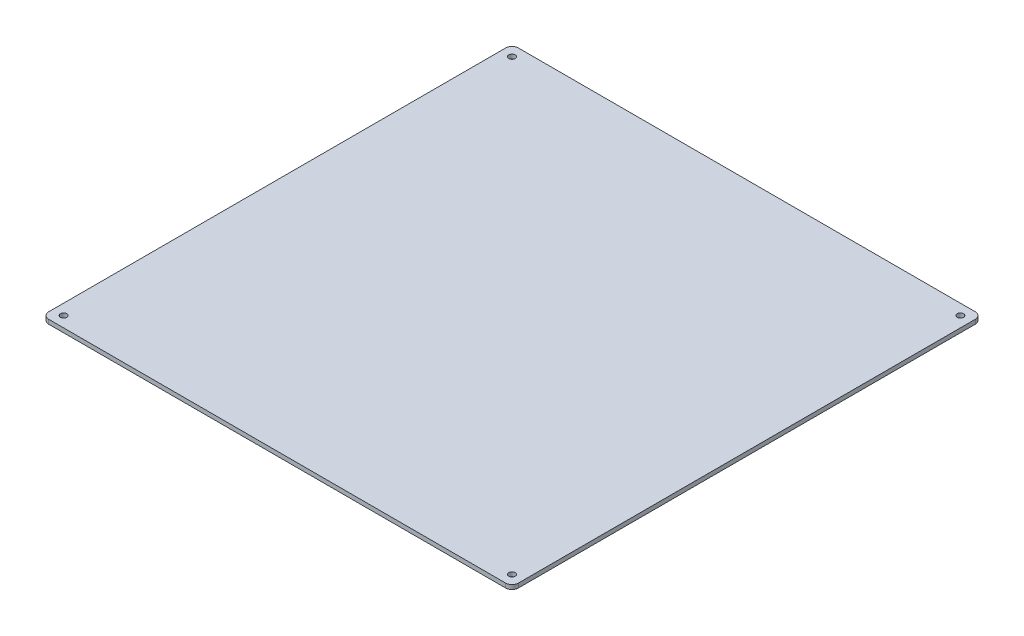
SolidWorks part; units mm, degrees
ref_plane "정면" through (0, 0, 0) normal (0, 0, 1) x (1, 0, 0)
ref_plane "윗면" through (0, 0, 0) normal (0, 1, 0) x (1, 0, 0)
ref_plane "우측면" through (0, 0, 0) normal (1, 0, 0) x (0, 0, -1)
sketch "스케치1" plane through (0, 0, 0) normal (0, 1, 0) x (1, 0, 0)
  line L0 (-109.5, 0) -> (109.5, 0) construction
  line L1 (-109.5, -109.5) -> (109.5, -109.5)
  line L2 (-109.5, -109.5) -> (-109.5, 109.5)
  line L3 (-109.5, 109.5) -> (109.5, 109.5)
  line L4 (109.5, -109.5) -> (109.5, 109.5)
  line L5 (-109.5, -109.5) -> (109.5, 109.5) construction
  line L6 (-109.5, 109.5) -> (109.5, -109.5) construction
  line L7 (-104.5, -104.5) -> (104.5, -104.5) construction
  line L8 (-104.5, -104.5) -> (-104.5, 104.5) construction
  line L9 (-104.5, 104.5) -> (104.5, 104.5) construction
  line L10 (104.5, -104.5) -> (104.5, 104.5) construction
  line L11 (-104.5, -104.5) -> (104.5, 104.5) construction
  line L12 (-104.5, 104.5) -> (104.5, -104.5) construction
  line L13 (0, 109.5) -> (0, -109.5) construction
  circle A0 centre (-104.5, 104.5) radius 1.5
  circle A1 centre (-104.5, -104.5) radius 1.5
  circle A2 centre (104.5, -104.5) radius 1.5
  circle A3 centre (104.5, 104.5) radius 1.5
  point P0 (0, 0)
  point P6 (0, 0)
  dimension "D3" = 3
  dimension "D1" = 219
  dimension "D2" = 209
extrude "보스-돌출1" add sketch "스케치1" along normal blind 2
fillet "필렛1" radius 3 4 edges at (-109.5, 1, -109.5) (109.5, 1, -109.5) (-109.5, 1, 109.5) (109.5, 1, 109.5)
